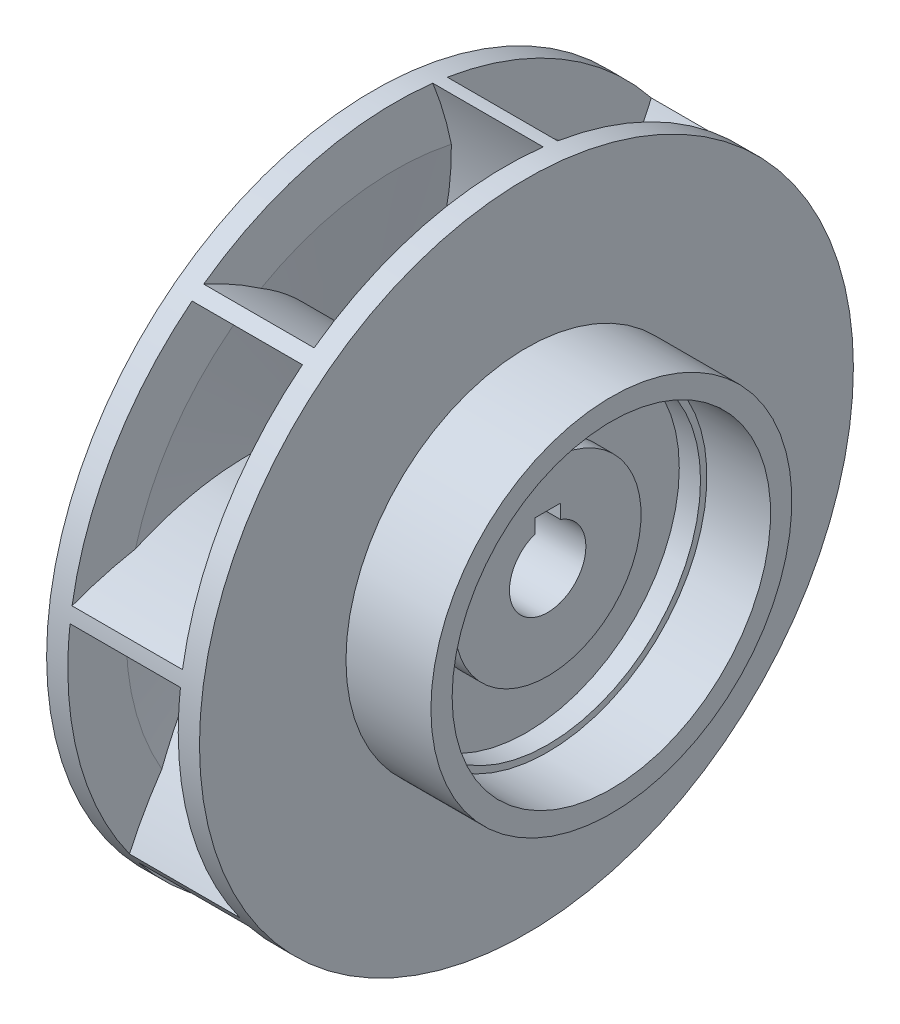
SolidWorks part; units mm, degrees
ref_plane "Front Plane" through (0, 0, 0) normal (0, 0, 1) x (1, 0, 0)
ref_plane "Top Plane" through (0, 0, 0) normal (0, 1, 0) x (1, 0, 0)
ref_plane "Right Plane" through (0, 0, 0) normal (1, 0, 0) x (0, 0, -1)
sketch "Sketch1" plane through (0, 0, 0) normal (0, 0, 1) x (1, 0, 0)
  line L0 (-33.4286, 0) -> (33.489, 0) construction
  line L1 (0, 9) -> (32, 9)
  line L2 (32, 9) -> (32, 22)
  line L3 (32, 22) -> (27, 22)
  line L4 (27, 22) -> (27, 36)
  line L5 (27, 36) -> (32, 36)
  line L6 (32, 36) -> (32, 37.5)
  line L7 (32, 37.5) -> (47, 37.5)
  line L8 (47, 37.5) -> (47, 42.5)
  line L9 (47, 42.5) -> (27, 42.5)
  line L10 (27, 42.5) -> (27, 77)
  line L11 (27, 77) -> (22, 77)
  line L12 (22, 77) -> (22, 62.2211)
  line L13 (0, 9) -> (0, 26.5)
  arc A0 (0, 26.5) -> (22, 62.2211) centre (-18, 62.2211) ccw
  point P4 (0, 0)
  dimension "D13" = 40
  dimension "D1" = 18
  dimension "D2" = 44
  dimension "D3" = 72
  dimension "D4" = 75
  dimension "D5" = 85
  dimension "D6" = 154
  dimension "D7" = 5
  dimension "D8" = 5
  dimension "D9" = 15
  dimension "D10" = 20
  dimension "D11" = 5
  dimension "D12" = 17.5
  dimension "D14" = 32
revolve "Revolve1" add sketch "Sketch1" angle 360 about L0
sketch "Sketch2" plane through (22, 0, 0) normal (-1, 0, 0) x (0, 0, 1)
  arc A0 (16.1776, 9.9642) -> (14.3258, 12.4809) centre (0, 0) ccw
  arc A2 (76.0018, 12.3583) -> (14.3258, 12.4809) centre (45, -70) ccw
  arc A3 (76.4773, 8.9568) -> (16.1776, 9.9642) centre (45, -70) ccw
  circle A4 centre (0, 0) radius 77 construction
  arc A5 (76.4773, 8.9568) -> (76.0018, 12.3583) centre (0, 0) ccw
  dimension "D1" = 170
  dimension "D2" = 176
  dimension "D5" = 38
  dimension "D3" = 70
  dimension "D4" = 45
extrude "Boss-Extrude1" add sketch "Sketch2" along normal blind 34
fillet "Fillet2" radius 5 1 edges at (-12, 11.2607, 15.3035)
pattern_circular "CirPattern1" count 8 over 360 about axis through (0, 0, 0) along (1, 0, 0) of "Boss-Extrude1", "Fillet2"
sketch "Sketch3" plane through (0, 0, 0) normal (0, 0, 1) x (1, 0, 0)
  line L0 (-68.482, 0) -> (68.5068, 0) construction
  line L1 (-10.4671, 30) -> (-33, 30)
  line L2 (-33, 30) -> (-33, 35)
  line L3 (-33, 35) -> (-18, 35)
  line L4 (-18, 35) -> (-18, 37)
  line L5 (-18, 37) -> (-14.2, 37)
  line L6 (-14.2, 37) -> (-9, 63.7517)
  line L7 (-9, 63.7517) -> (-9, 77)
  line L8 (-9, 77) -> (-4, 77)
  line L9 (-4, 77) -> (-4, 63.2702)
  line L10 (-4, 63.2702) -> (-10.4671, 30)
  line L11 (22, 76.0018) -> (22, 47.7442) construction
  point P4 (0, 0)
  dimension "D1" = 15
  dimension "D2" = 5
  dimension "D3" = 26
  dimension "D4" = 11
  dimension "D5" = 33
  dimension "D6" = 18.8
  dimension "D7" = 70
  dimension "D8" = 74
  dimension "D9" = 154
  dimension "D10" = 5
  dimension "D11" = 5
revolve "Revolve2" add sketch "Sketch3" angle 360 about L0
sketch "Sketch4" plane through (0, 0, 0) normal (0, 0, 1) x (1, 0, 0)
  line L1 (-18, 37) -> (-14.2, 37)
  line L2 (-9, 63.7517) -> (-14.2, 37) construction
  line L3 (-9, 63.7517) -> (-14.2, 37)
  line L4 (-9, 77) -> (-9, 62.48) construction
  line L5 (-9, 77) -> (-9, 63.7517)
  line L6 (-9, 77) -> (-18, 77)
  line L7 (-18, 77) -> (-18, 37)
  line L8 (-70.5431, 0) -> (70.5649, 0) construction
  point P12 (0, 0)
revolve "Cut-Revolve1" cut sketch "Sketch4" angle 360 about L8
sketch "Sketch5" plane through (0, 0, 0) normal (1, 0, 0) x (0, 0, -1)
  line L1 (-3, 11.8) -> (3, 11.8)
  line L2 (-3, 11.8) -> (-3, 6.2)
  line L3 (-3, 6.2) -> (3, 6.2)
  line L4 (3, 11.8) -> (3, 6.2)
  line L5 (-3, 11.8) -> (3, 6.2) construction
  line L6 (-3, 6.2) -> (3, 11.8) construction
  circle A0 centre (0, 0) radius 9 construction
  circle A1 centre (0, 0) radius 9
  point P3 (0, 9)
  dimension "D1" = 6
  dimension "D2" = 11.8
extrude "Cut-Extrude1" cut sketch "Sketch5" along normal through all both and the other way through all contours L1 L4 L3 L2
